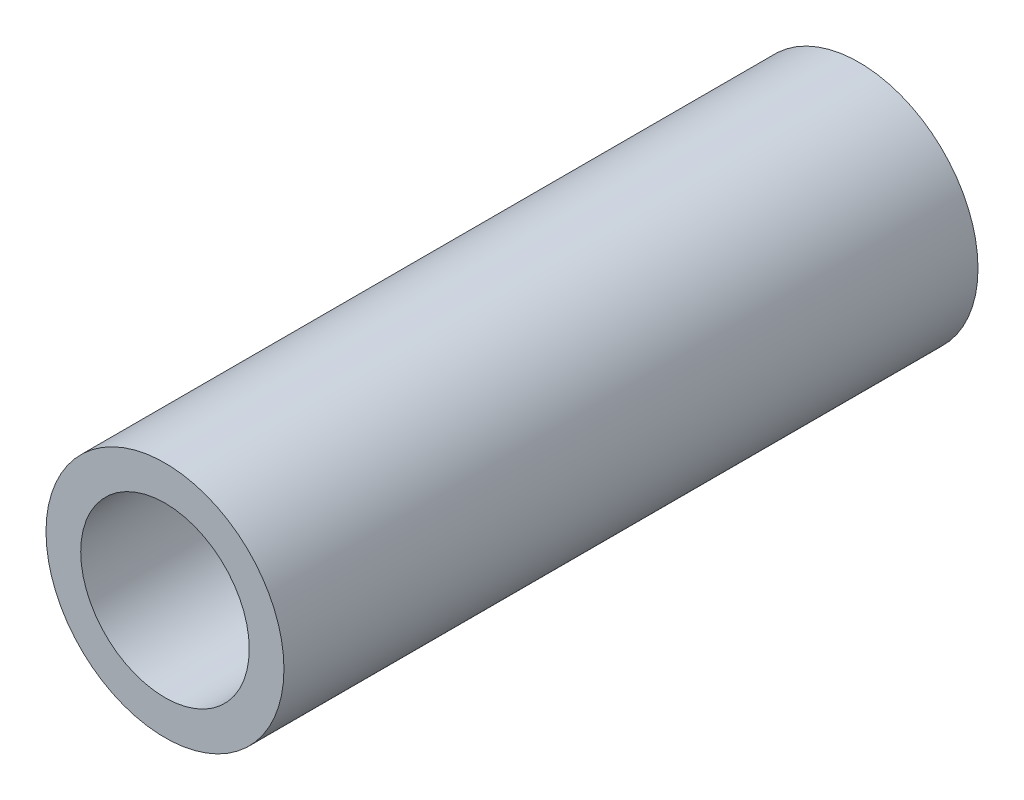
SolidWorks part; units mm, degrees
material "PVC blau"
ref_plane "Ebene1" through (0, 0, 0) normal (0, 0, 1) x (1, 0, 0)
ref_plane "Ebene2" through (0, 0, 0) normal (0, 1, 0) x (1, 0, 0)
ref_plane "Ebene3" through (0, 0, 0) normal (1, 0, 0) x (0, 0, -1)
sketch "Skizze1" plane through (0, 0, 0) normal (1, 0, 0) x (0, 0, -1)
  line L0 (-75.6783, 0) -> (76.9789, 0) construction
  line L1 (0, 4.25) -> (0, 0) construction
  line L2 (-17.5, 6) -> (17.5, 6)
  line L3 (-17.5, 6) -> (-17.5, 4.25)
  line L4 (-17.5, 4.25) -> (17.5, 4.25)
  line L5 (17.5, 6) -> (17.5, 4.25)
  dimension "D1" = 35
  dimension "D2" = 1.75
  dimension "D3" = 12
  dimension "D4" = 8.5
revolve "Rotation1" add sketch "Skizze1" angle 360 about L0
